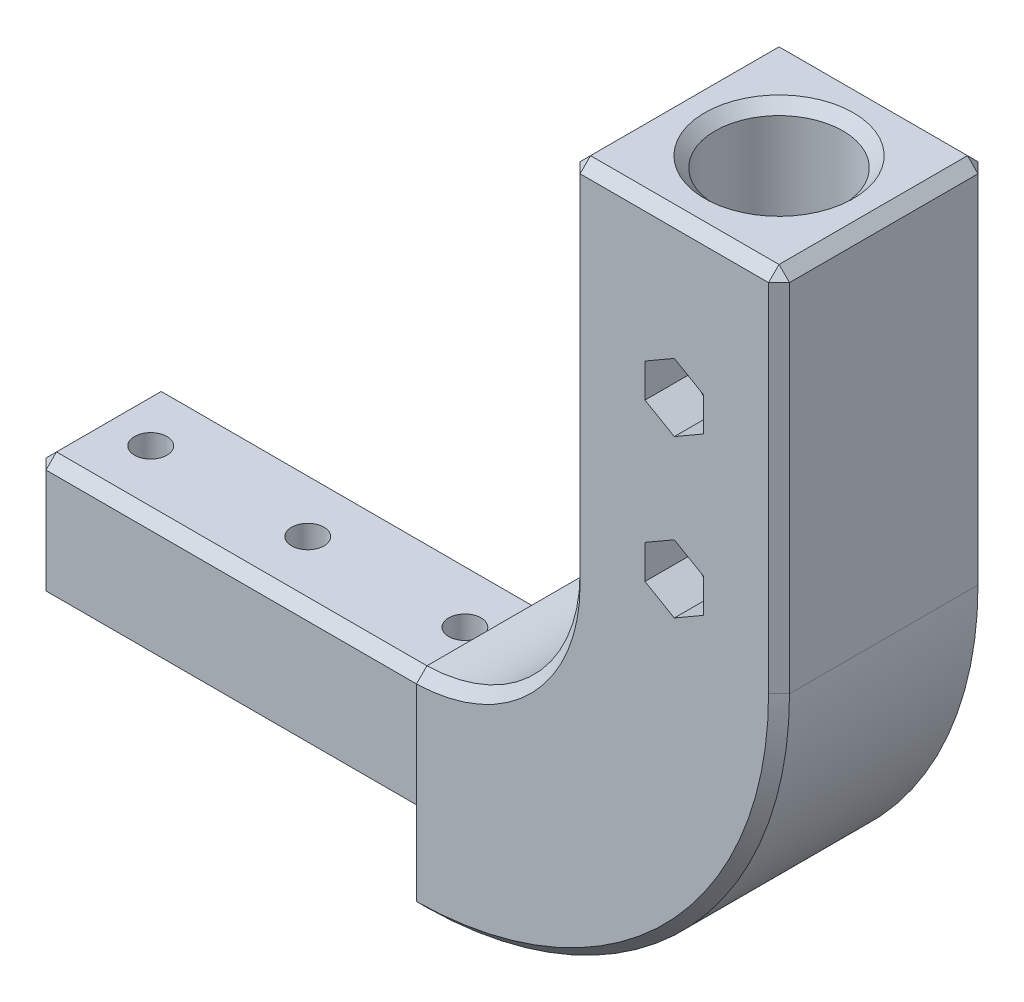
SolidWorks part; units mm, degrees
material "ABS"
ref_plane "前视基准面" through (0, 0, 0) normal (0, 0, 1) x (1, 0, 0)
ref_plane "上视基准面" through (0, 0, 0) normal (0, 1, 0) x (1, 0, 0)
ref_plane "右视基准面" through (0, 0, 0) normal (1, 0, 0) x (0, 0, -1)
other "Configuration Table"
sketch "草图13" plane through (0, 0, 0) normal (0, 0, 1) x (1, 0, 0)
  line L10 (0, 10) -> (45, 10) construction
  line L11 (0, 0) -> (45, 0)
  line L12 (0, 0) -> (0, 20)
  line L13 (0, 20) -> (45, 20)
  line L14 (45, 0) -> (45, 20) construction
  line L15 (45, 10) -> (65, 10) construction
  line L16 (65, 10) -> (65, 30) construction
  line L17 (65, 30) -> (65, 70) construction
  line L18 (55, 70) -> (75, 70)
  line L19 (55, 70) -> (55, 20)
  line L20 (55, 20) -> (45, 20)
  line L21 (75, 70) -> (75, 0)
  line L22 (75, 0) -> (45, 0)
  circle A0 centre (5, 10) radius 1.55 construction
  circle A1 centre (20, 10) radius 1.55 construction
  circle A2 centre (35, 10) radius 1.55 construction
  circle A3 centre (65, 40) radius 1.55
  circle A4 centre (65, 55) radius 1.55
  dimension "D3" = 3.1
  dimension "D4" = 3.1
  dimension "D5" = 3.1
  dimension "D14" = 3.1
  dimension "D16" = 3.1
  dimension "D1" = 45
  dimension "D2" = 20
  dimension "D6" = 5
  dimension "D7" = 15
  dimension "D8" = 15
  dimension "D9" = 20
  dimension "D10" = 20
  dimension "D11" = 40
  dimension "D12" = 10
  dimension "D13" = 10
  dimension "D15" = 10
  dimension "D17" = 15
extrude "凸台-拉伸6" add sketch "草图13" along normal blind 20
sketch "草图14" plane through (0, 0, 0) normal (-1, 0, 0) x (0, 0, 1)
  line L8 (3.9, 16.1) -> (3.9, 3.9)
  line L9 (3.9, 3.9) -> (16.1, 3.9)
  line L10 (16.1, 3.9) -> (16.1, 16.1)
  line L11 (16.1, 16.1) -> (3.9, 16.1)
  line L12 (3.9, 16.1) -> (3.9, 3.9)
  line L13 (3.9, 3.9) -> (16.1, 3.9)
  line L14 (16.1, 3.9) -> (16.1, 16.1)
  line L15 (16.1, 16.1) -> (3.9, 16.1)
  dimension "D1" = 3.9
extrude "切除-拉伸3" [suppressed] cut sketch "草图14" against normal blind 40.1
sketch "草图15" plane through (0, 70, 0) normal (0, 1, 0) x (1, 0, 0)
  line L0 (55, -20) -> (55, 0) construction
  line L1 (75, -20) -> (55, -20) construction
  circle A0 centre (65, -10) radius 6.1
  dimension "D1" = 12.2
  dimension "D2" = 10
  dimension "D3" = 10
extrude "切除-拉伸4" cut sketch "草图15" against normal blind 40.1
sketch "草图16" plane through (0, 20, 0) normal (0, 1, 0) x (1, 0, 0)
  line L0 (0, -10) -> (55, -10) construction
  line L1 (0, -20) -> (0, 0) construction
  line L2 (55, -20) -> (55, 0) construction
  circle A0 centre (5, -10) radius 1.55
  circle A1 centre (20, -10) radius 1.55
  circle A2 centre (35, -10) radius 1.55
  dimension "D3" = 3.1
  dimension "D4" = 3.1
  dimension "D5" = 3.1
  dimension "D1" = 15
  dimension "D2" = 15
  dimension "D6" = 5
extrude "切除-拉伸5" cut sketch "草图16" against normal through all
chamfer "倒角2" [suppressed] distance 10 angle 45
chamfer "倒角4" [suppressed] distance 20 angle 45
chamfer "倒角5" [suppressed] distance 1 angle 45
sketch "草图22" plane through (0, 0, 0) normal (0, 0, -1) x (-1, 0, 0)
  line L4 (-75, 0) -> (-75, 70) construction
  line L6 (0, 0) -> (-75, 0) construction
  line L7 (-55, 70) -> (-55, 20) construction
  line L8 (-75, 35) -> (-75, 70) construction
  line L9 (-75, 70) -> (-55, 70) construction
  line L10 (-55, 70) -> (-55, 45) construction
  line L11 (-30.6101, 20) -> (0, 20) construction
  line L12 (0, 20) -> (0, 0) construction
  line L13 (0, 0) -> (-40, 0) construction
  line L18 (-55, 20) -> (0, 20) construction
sketch "草图24" plane through (0, 0, 0) normal (0, 0, -1) x (-1, 0, 0)
  line L0 (-75, 0) -> (-75, 70) construction
  line L1 (0, 0) -> (-75, 0) construction
  line L2 (0, 0) -> (-40, 0) construction
  line L3 (-75, 35) -> (-75, 0)
  line L4 (-75, 0) -> (-40, 0)
  arc A0 (-75, 35) -> (-40, 0) centre (-40, 35) ccw
  dimension "D1" = 35
  dimension "D2" = 35
  dimension "D3" = 35
extrude "切除-拉伸7" cut sketch "草图24" against normal through all
sketch "草图25" plane through (0, 0, 0) normal (0, 0, -1) x (-1, 0, 0)
  line L0 (-55, 70) -> (-55, 20) construction
  line L1 (-55, 20) -> (0, 20) construction
  line L2 (-55, 34.9953) -> (-55, 20)
  line L3 (-55, 20) -> (-40.3768, 20)
  arc A0 (-55, 34.9953) -> (-40.3768, 20) centre (-40, 34.9953) ccw
  dimension "D1" = 15
  dimension "D2" = 15
  dimension "D3" = 14.9953
extrude "凸台-拉伸8" add sketch "草图25" against normal up to surface (20 mm away) up to face at (43.8927, 29.6788, 20)
chamfer "倒角6" [suppressed] distance 1 angle 45
sketch "草图26" plane through (0, 0, 0) normal (0, -1, 0) x (1, 0, 0)
  line L1 (4.0447, 6.9112) -> (7.1973, 7.6282)
  line L2 (7.1973, 7.6282) -> (8.1526, 10.717)
  line L3 (8.1526, 10.717) -> (5.9553, 13.0888)
  line L4 (5.9553, 13.0888) -> (2.8027, 12.3718)
  line L5 (2.8027, 12.3718) -> (1.8474, 9.283)
  line L6 (1.8474, 9.283) -> (4.0447, 6.9112)
  line L7 (19.0447, 6.9112) -> (22.1973, 7.6282)
  line L8 (22.1973, 7.6282) -> (23.1526, 10.717)
  line L9 (23.1526, 10.717) -> (20.9553, 13.0888)
  line L10 (20.9553, 13.0888) -> (17.8027, 12.3718)
  line L11 (17.8027, 12.3718) -> (16.8474, 9.283)
  line L12 (16.8474, 9.283) -> (19.0447, 6.9112)
  line L13 (34.0447, 6.9112) -> (37.1973, 7.6282)
  line L14 (37.1973, 7.6282) -> (38.1526, 10.717)
  line L15 (38.1526, 10.717) -> (35.9553, 13.0888)
  line L16 (35.9553, 13.0888) -> (32.8027, 12.3718)
  line L17 (32.8027, 12.3718) -> (31.8474, 9.283)
  line L18 (31.8474, 9.283) -> (34.0447, 6.9112)
  circle A0 centre (5, 10) radius 2.8 construction
  circle A1 centre (20, 10) radius 2.8 construction
  circle A2 centre (35, 10) radius 2.8 construction
  dimension "D1" = 5.6
  dimension "D2" = 5.6
  dimension "D3" = 5.6
extrude "切除-拉伸8" cut sketch "草图26" against normal blind 4
sketch "草图27" plane through (0, 0, 20) normal (0, 0, -1) x (-1, 0, 0)
  line L1 (-65, 36.7668) -> (-62.2, 38.3834)
  line L2 (-62.2, 38.3834) -> (-62.2, 41.6166)
  line L3 (-62.2, 41.6166) -> (-65, 43.2332)
  line L4 (-65, 43.2332) -> (-67.8, 41.6166)
  line L5 (-67.8, 41.6166) -> (-67.8, 38.3834)
  line L6 (-67.8, 38.3834) -> (-65, 36.7668)
  line L7 (-65, 51.7668) -> (-62.2, 53.3834)
  line L8 (-62.2, 53.3834) -> (-62.2, 56.6166)
  line L9 (-62.2, 56.6166) -> (-65, 58.2332)
  line L10 (-65, 58.2332) -> (-67.8, 56.6166)
  line L11 (-67.8, 56.6166) -> (-67.8, 53.3834)
  line L12 (-67.8, 53.3834) -> (-65, 51.7668)
  circle A0 centre (-65, 40) radius 2.8 construction
  circle A1 centre (-65, 55) radius 2.8 construction
  dimension "D1" = 5.6
  dimension "D2" = 5.6
extrude "切除-拉伸9" cut sketch "草图27" along normal blind 5
sketch "草图28" plane through (0, 0, 20) normal (0, 0, 1) x (1, 0, 0)
  line L0 (0, 10) -> (20, 10) construction
  line L1 (0, 20) -> (0, 0) construction
  line L3 (12, 12.5) -> (28, 12.5)
  line L4 (10, 10.5) -> (10, 9.5)
  line L5 (12, 7.5) -> (28, 7.5)
  line L6 (30, 10.5) -> (30, 9.5)
  line L7 (10, 12.5) -> (30, 7.5) construction
  line L8 (10, 7.5) -> (30, 12.5) construction
  arc A0 (10, 9.5) -> (12, 7.5) centre (12, 9.5) ccw
  arc A1 (28, 7.5) -> (30, 9.5) centre (28, 9.5) ccw
  arc A2 (28, 12.5) -> (30, 10.5) centre (28, 10.5) cw
  arc A3 (12, 12.5) -> (10, 10.5) centre (12, 10.5) ccw
  dimension "D4" = 2
  dimension "D1" = 20
  dimension "D2" = 20
  dimension "D3" = 5
extrude "切除-拉伸10" [suppressed] cut sketch "草图28" against normal through all
sketch "草图29" plane through (0, 0, 0) normal (-1, 0, 0) x (0, 0, 1)
  line L5 (0, 20) -> (20, 20)
  line L6 (0, 20) -> (0, 0)
  line L7 (0, 0) -> (20, 0)
  line L8 (4, 16) -> (4, 4)
  line L10 (4, 16) -> (4, 4)
  line L16 (20, 20) -> (20, 0)
  line L20 (4, 4) -> (16, 4)
  line L22 (4, 4) -> (16, 4)
  line L24 (16, 4) -> (16, 16)
  line L25 (16, 4) -> (16, 16)
  line L26 (16, 16) -> (4, 16)
  line L27 (16, 16) -> (4, 16)
  dimension "D1" = 4
extrude "切除-拉伸11" cut sketch "草图29" against normal up to vertex (40.3768 mm away)
chamfer "倒角7" distance 1 angle 45 21 edges at (65, 70, 16.1) (0, 10, 16) (20.1884, 4, 16) (0, 16, 10) (0, 4, 10) (20.1884, 4, 4) (0, 10, 4) (20.1884, 16, 4) (20.1884, 16, 16) (64.8816, 10.3849, 20) (64.8816, 10.3849, 0) (50.739, 24.5227, 0) (50.739, 24.5227, 20) (75, 70, 10) (75, 52.5, 20) (65, 70, 20) (75, 52.5, 0) (65, 70, 0) (55, 52.4976, 0) (55, 52.4976, 20) (55, 70, 10)
